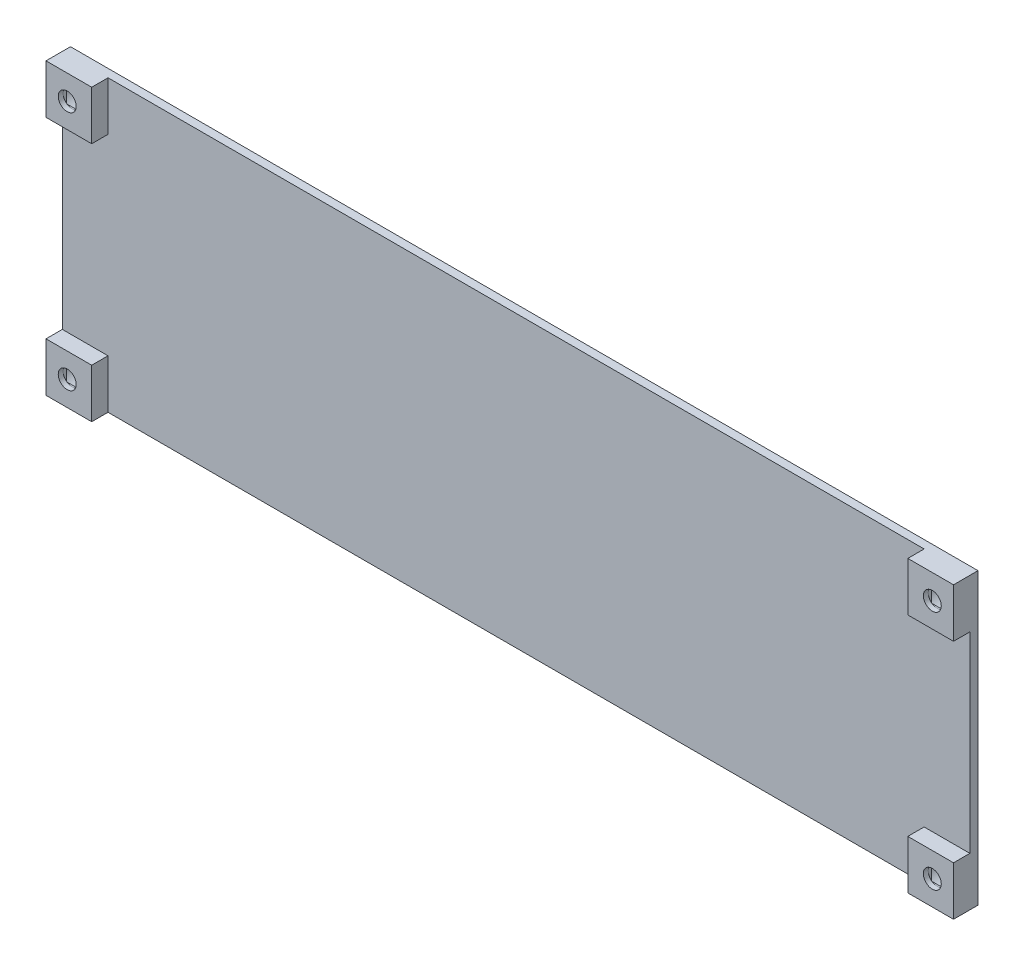
SolidWorks part; units mm, degrees
ref_plane "Front Plane" through (0, 0, 0) normal (0, 0, 1) x (1, 0, 0)
ref_plane "Top Plane" through (0, 0, 0) normal (0, 1, 0) x (1, 0, 0)
ref_plane "Right Plane" through (0, 0, 0) normal (1, 0, 0) x (0, 0, -1)
sketch "Sketch1" plane through (0, 0, 0) normal (0, 0, 1) x (1, 0, 0)
  line L1 (-56, -17.75) -> (56, -17.75)
  line L2 (-56, -17.75) -> (-56, 17.75)
  line L3 (-56, 17.75) -> (56, 17.75)
  line L4 (56, -17.75) -> (56, 17.75)
  line L5 (-56, -17.75) -> (56, 17.75) construction
  line L6 (-56, 17.75) -> (56, -17.75) construction
  point P0 (0, 0)
  dimension "D1" = 112
  dimension "D2" = 35.5
extrude "Boss-Extrude1" add sketch "Sketch1" along normal blind 1
sketch "Sketch2" plane through (0, 0, 1) normal (0, 0, 1) x (1, 0, 0)
  line L0 (0, -17.75) -> (0, 17.75) construction
  line L1 (-56, 17.75) -> (-50, 17.75)
  line L2 (-56, 17.75) -> (-56, 11.75)
  line L3 (-56, 11.75) -> (-50, 11.75)
  line L4 (-50, 17.75) -> (-50, 11.75)
  line L5 (-56, -17.75) -> (56, -17.75) construction
  line L6 (56, 17.75) -> (-56, 17.75) construction
  line L7 (-56, 0) -> (56, 0) construction
  line L8 (-56, 17.75) -> (-56, -17.75) construction
  line L9 (56, -17.75) -> (56, 17.75) construction
  line L10 (-50, -17.75) -> (-50, -11.75)
  line L11 (-56, -11.75) -> (-50, -11.75)
  line L12 (-56, -17.75) -> (-56, -11.75)
  line L13 (-56, -17.75) -> (-50, -17.75)
  line L14 (56, -17.75) -> (50, -17.75)
  line L15 (56, -17.75) -> (56, -11.75)
  line L16 (56, -11.75) -> (50, -11.75)
  line L17 (50, -17.75) -> (50, -11.75)
  line L18 (50, 17.75) -> (50, 11.75)
  line L19 (56, 11.75) -> (50, 11.75)
  line L20 (56, 17.75) -> (56, 11.75)
  line L21 (56, 17.75) -> (50, 17.75)
  dimension "D1" = 6
extrude "Boss-Extrude2" add sketch "Sketch2" along normal blind 2
sketch "Sketch3" plane through (0, 0, 3) normal (0, 0, 1) x (1, 0, 0)
  line L0 (-56, 0) -> (56, 0) construction
  line L1 (-56, 11.75) -> (-56, -11.75) construction
  line L2 (56, -11.75) -> (56, 11.75) construction
  line L3 (0, 17.75) -> (0, -17.75) construction
  line L4 (50, 17.75) -> (-50, 17.75) construction
  line L5 (-50, -17.75) -> (50, -17.75) construction
  line L6 (-56, 11.75) -> (-50, 17.75) construction
  line L7 (-56, -11.75) -> (-50, -17.75) construction
  line L8 (56, -11.75) -> (50, -17.75) construction
  line L9 (56, 11.75) -> (50, 17.75) construction
  circle A0 centre (-53, 14.75) radius 1.1
  circle A1 centre (-53, -14.75) radius 1.1
  circle A2 centre (53, -14.75) radius 1.1
  circle A3 centre (53, 14.75) radius 1.1
  dimension "D1" = 2.2
extrude "Cut-Extrude1" cut sketch "Sketch3" against normal through all
sketch "Sketch4" plane through (0, 0, 0) normal (0, 0, -1) x (-1, 0, 0)
  circle A0 centre (-53, 14.75) radius 2
  circle A1 centre (-53, -14.75) radius 2
  circle A2 centre (53, 14.75) radius 2
  circle A3 centre (53, -14.75) radius 2
  dimension "D1" = 4
extrude "Cut-Extrude2" cut sketch "Sketch4" against normal blind 2
sketch "Sketch5" plane through (0, 0, 2) normal (0, 0, -1) x (-1, 0, 0)
  line L2 (-54.1, 13.0797) -> (-54.1, 16.4203)
  line L4 (-51.9, 13.0797) -> (-51.9, 16.4203)
  line L5 (-54.1, 13.0797) -> (-51.9, 16.4203) construction
  line L6 (-54.1, 16.4203) -> (-51.9, 13.0797) construction
  circle A0 centre (-53, 14.75) radius 2 construction
  circle A1 centre (-53, 14.75) radius 1.1 construction
  circle A2 centre (-53, 14.75) radius 2 construction
  arc A3 (-51.9, 16.4203) -> (-54.1, 16.4203) centre (-53, 14.75) ccw
  arc A4 (-54.1, 13.0797) -> (-51.9, 13.0797) centre (-53, 14.75) ccw
  point P0 (-53, 14.75)
extrude "Cut-Extrude3" cut sketch "Sketch5" against normal blind 0.2
sketch "Sketch6" plane through (0, 0, 2.2) normal (0, 0, -1) x (-1, 0, 0)
  line L0 (-51.9, 13.0797) -> (-51.9, 16.4203) construction
  line L1 (-54.1, 13.65) -> (-51.9, 13.65)
  line L2 (-54.1, 13.65) -> (-54.1, 15.85)
  line L3 (-54.1, 15.85) -> (-51.9, 15.85)
  line L4 (-51.9, 13.65) -> (-51.9, 15.85)
  line L5 (-54.1, 13.65) -> (-51.9, 15.85) construction
  line L6 (-54.1, 15.85) -> (-51.9, 13.65) construction
  arc A0 (-51.9, 14.75) -> (-54.1, 14.75) centre (-53, 14.75) ccw construction
  point P0 (-53, 14.75)
extrude "Cut-Extrude4" cut sketch "Sketch6" against normal blind 0.2
mirror "Mirror1" about plane through (0, 0, 0) normal (1, 0, 0) of "Cut-Extrude4", "Cut-Extrude3"
mirror "Mirror2" about plane through (0, 0, 0) normal (0, 1, 0) of "Mirror1", "Cut-Extrude3", "Cut-Extrude4"
sketch "Sketch7" plane through (0, 0, 0) normal (0, 0, -1) x (-1, 0, 0)
  line L0 (56, -17.75) -> (-56, -17.75) construction
  line L1 (-56, 17.75) -> (-55.6, 17.75)
  line L2 (-56, 17.75) -> (-56, -17.75)
  line L3 (-56, -17.75) -> (-55.6, -17.75)
  line L4 (-55.6, 17.75) -> (-55.6, -17.75)
  line L6 (56, 17.75) -> (55.6, 17.75)
  line L7 (56, 17.75) -> (56, -17.75)
  line L8 (56, -17.75) -> (55.6, -17.75)
  line L9 (55.6, 17.75) -> (55.6, -17.75)
  dimension "D1" = 0.4
extrude "Cut-Extrude5" cut sketch "Sketch7" against normal through all
